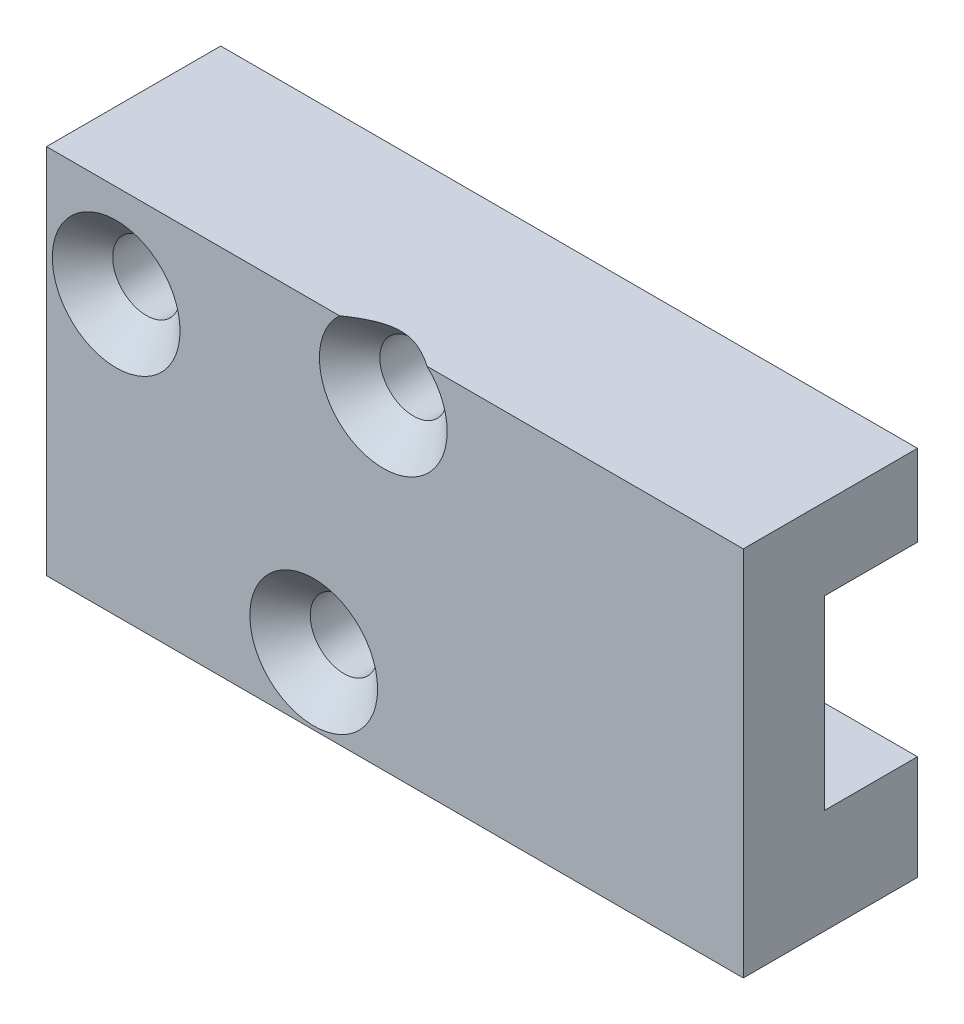
SolidWorks part; units mm, degrees
ref_plane "Front Plane" through (0, 0, 0) normal (0, 0, 1) x (1, 0, 0)
ref_plane "Top Plane" through (0, 0, 0) normal (0, 1, 0) x (1, 0, 0)
ref_plane "Right Plane" through (0, 0, 0) normal (1, 0, 0) x (0, 0, -1)
ref_plane "Plane1" through (0, 0, 0.5791) normal (0, 0, 1) x (1, 0, 0)
sketch "Sketch1" plane through (0, 0, 0.5791) normal (0, 0, 1) x (1, 0, 0)
  line L0 (129.395, -23.8061) -> (107.4, -23.8061) construction
  line L1 (129.395, -19.3061) -> (129.395, -23.8061) construction
  line L2 (116.395, -19.3061) -> (129.395, -19.3061) construction
  line L3 (116.395, -18.3061) -> (116.395, -19.3061) construction
  line L4 (110.395, -18.3061) -> (116.395, -18.3061) construction
  line L5 (107.4, -23.8061) -> (107.4, -21.0061) construction
  line L6 (101.4, -21.0061) -> (101.4, -23.8061) construction
  line L7 (101.4, -23.8061) -> (99.395, -23.8061) construction
  line L8 (99.395, -7.8061) -> (99.395, -23.8061) construction
  line L9 (129.395, -7.8061) -> (99.395, -7.8061) construction
  line L10 (129.395, -7.8061) -> (129.395, -11.3061) construction
  line L11 (129.395, -11.3061) -> (116.395, -11.3061) construction
  line L12 (116.395, -11.3061) -> (116.395, -12.3061) construction
  line L13 (116.395, -12.3061) -> (110.395, -12.3061) construction
  line L14 (129.395, -23.8061) -> (107.4, -23.8061)
  line L15 (129.395, -19.3061) -> (129.395, -23.8061)
  line L16 (116.395, -19.3061) -> (129.395, -19.3061)
  line L17 (116.395, -18.3061) -> (116.395, -19.3061)
  line L18 (110.395, -18.3061) -> (116.395, -18.3061)
  line L19 (107.4, -23.8061) -> (107.4, -21.0061)
  line L20 (101.4, -21.0061) -> (101.4, -23.8061)
  line L21 (101.4, -23.8061) -> (99.395, -23.8061)
  line L22 (99.395, -7.8061) -> (99.395, -23.8061)
  line L23 (129.395, -7.8061) -> (99.395, -7.8061)
  line L24 (129.395, -7.8061) -> (129.395, -11.3061)
  line L25 (129.395, -11.3061) -> (116.395, -11.3061)
  line L26 (116.395, -11.3061) -> (116.395, -12.3061)
  line L27 (116.395, -12.3061) -> (110.395, -12.3061)
  arc A0 (110.395, -18.3061) -> (107.4, -21.0061) centre (110.3849, -21.3061) ccw construction
  arc A1 (110.395, -12.3061) -> (101.4, -21.0061) centre (110.395, -21.3061) ccw construction
  arc A2 (110.395, -18.3061) -> (107.4, -21.0061) centre (110.3849, -21.3061) ccw
  arc A3 (110.395, -12.3061) -> (101.4, -21.0061) centre (110.395, -21.3061) ccw
  point P0 (110.9, -20.9061)
  point P2 (113.895, -9.8061)
  point P4 (102.395, -11.8061)
extrude "Boss-Extrude1" add sketch "Sketch1" along normal blind 4 contours L18 A2 L19 L14 L15 L16 L17 | L20 L21 L22 L23 L24 L25 L26 L27 A3
sketch "Sketch2" plane through (0, 0, 4.5791) normal (0, 0, 1) x (1, 0, 0)
  line L0 (99.395, -23.8061) -> (99.395, -7.8061)
  line L1 (99.395, -7.8061) -> (129.395, -7.8061)
  line L2 (129.395, -7.8061) -> (129.395, -23.8061)
  line L3 (129.395, -23.8061) -> (99.395, -23.8061)
extrude "Boss-Extrude2" add sketch "Sketch2" along normal blind 3.5
sketch "Sketch5" plane through (0, 0, 8.0791) normal (0, 0, 1) x (1, 0, 0)
  point P0 (102.395, -11.8061)
  point P1 (110.9, -20.9061)
  point P2 (113.895, -9.8061)
hole_wizard "CSK for M2.5 Countersunk Flat Head Screw1" positions "Sketch6" profile "Sketch7" countersink size "M2.5" standard "ISO" end condition up to next
sketch "Sketch6" plane through (0, 0, 8.0791) normal (0, 0, 1) x (1, 0, 0)
  point P0 (102.395, -11.8061)
  point P3 (113.895, -9.8061)
  point P6 (110.9, -20.9061)
sketch "Sketch7" plane through (102.395, -11.8061, 8.0791) normal (1, 0, 0) x (0, -1, 0)
  line L0 (0, 0) -> (0, 7.5)
  line L1 (0, 7.5) -> (1.45, 7.5)
  line L2 (1.45, 7.5) -> (1.45, 1.3)
  line L3 (1.45, 1.3) -> (2.75, 0)
  line L5 (2.75, 0) -> (0, 0)
  line L6 (-1.45, 1.3) -> (-2.75, 0) construction
  line L11 (0, -6.35) -> (0, 107.95) construction
  dimension "Thru Hole Dia." = 2.9
  dimension "Thru Hole Depth" = 7.5
  dimension "Near C'Sink Dia." = 5.5
  dimension "Near C'Sink Angle" = 90
